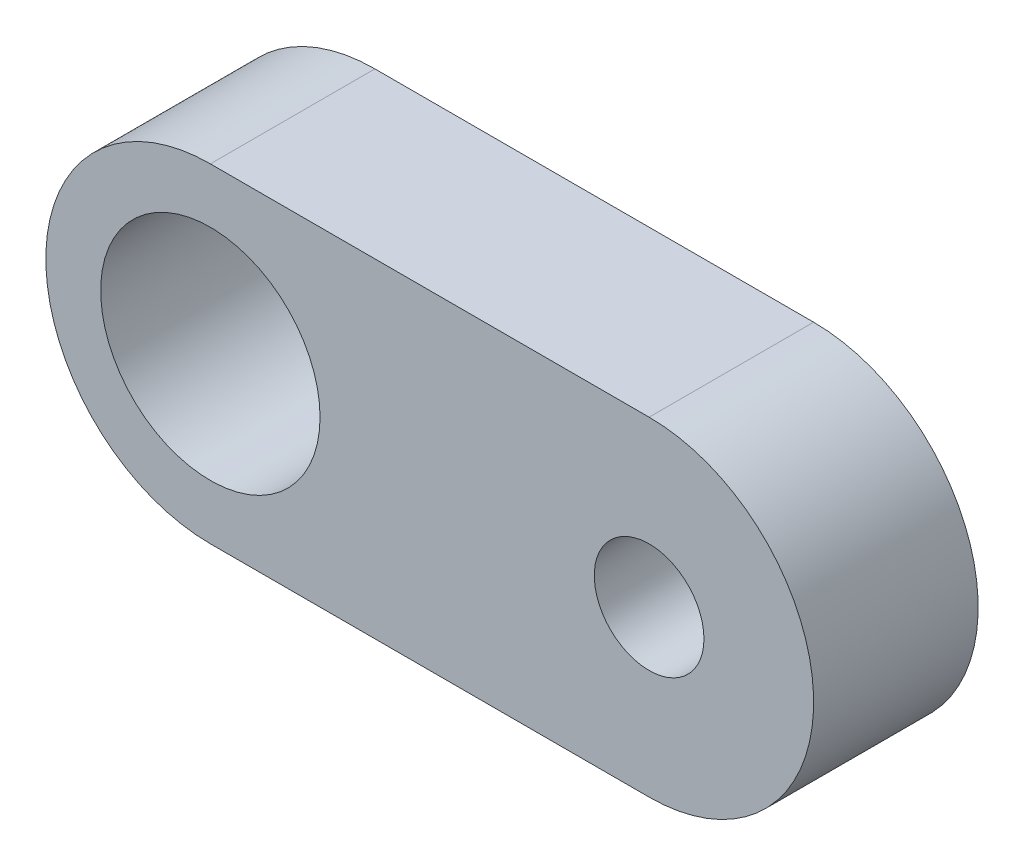
SolidWorks part; units mm, degrees
ref_plane "Front" through (0, 0, 0) normal (0, 0, 1) x (1, 0, 0)
ref_plane "Top" through (0, 0, 0) normal (0, 1, 0) x (1, 0, 0)
ref_plane "Right" through (0, 0, 0) normal (1, 0, 0) x (0, 0, -1)
sketch "Эскиз1" plane through (0, 0, 0) normal (0, 0, 1) x (1, 0, 0)
  line L0 (0, 3) -> (8, 3)
  line L2 (8, -3) -> (0, -3)
  circle A0 centre (0, 0) radius 2
  arc A1 (0, 3) -> (0, -3) centre (0, 0) ccw
  arc A2 (11, 0) -> (8, -3) centre (8, 0) cw
  arc A3 (8, 3) -> (11, 0) centre (8, 0) cw
  circle A4 centre (8, 0) radius 1
  dimension "D1" = 8
  dimension "D3" = 3
  dimension "D2" = 4
extrude "Бобышка-Вытянуть1" add sketch "Эскиз1" along normal blind 3
